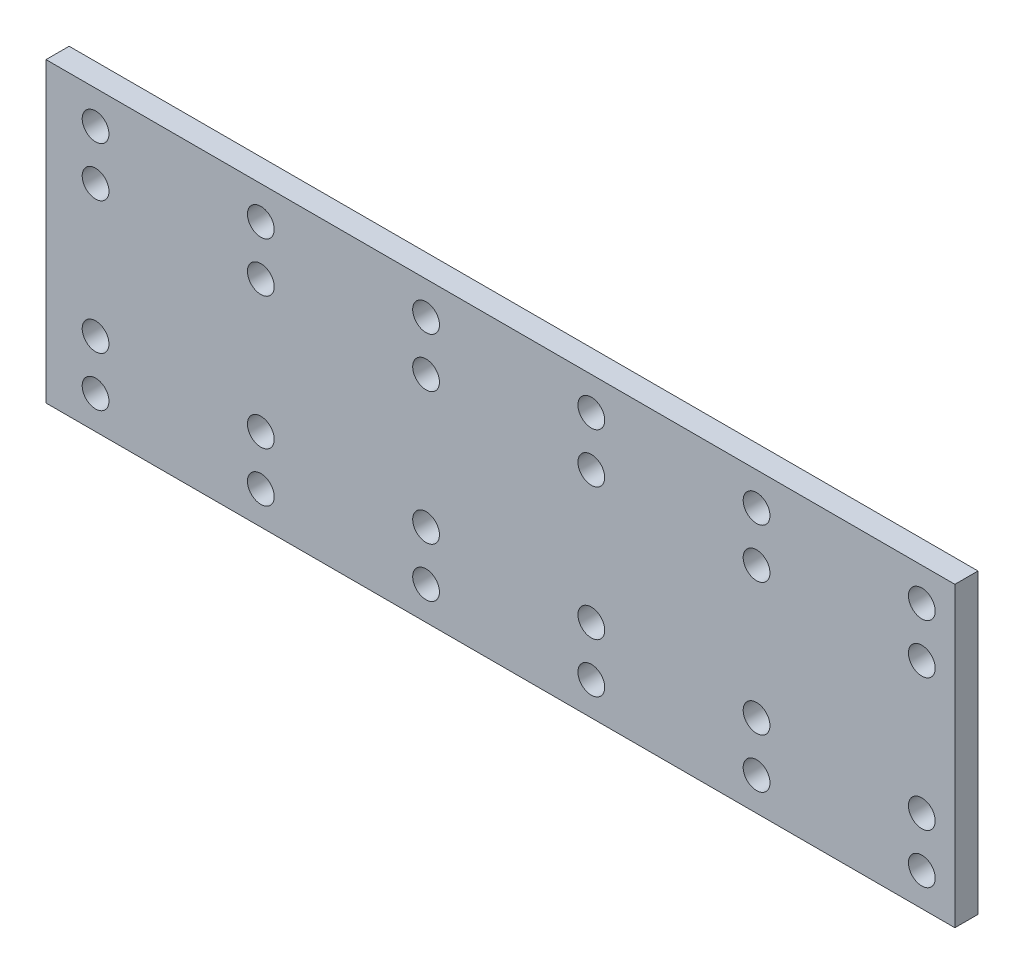
SolidWorks part; units mm, degrees
ref_plane "Front Plane" through (0, 0, 0) normal (0, 0, 1) x (1, 0, 0)
ref_plane "Top Plane" through (0, 0, 0) normal (0, 1, 0) x (1, 0, 0)
ref_plane "Right Plane" through (0, 0, 0) normal (1, 0, 0) x (0, 0, -1)
sketch "Sketch1" plane through (0, 0, 0) normal (0, 0, 1) x (1, 0, 0)
  line L1 (0, 0) -> (275, 0)
  line L2 (0, 0) -> (0, 90)
  line L3 (0, 90) -> (275, 90)
  line L4 (275, 0) -> (275, 90)
  dimension "D1" = 275
  dimension "D2" = 90
extrude "Boss-Extrude1" add sketch "Sketch1" along normal blind 7
sketch "Sketch2" plane through (0, 0, 7) normal (0, 0, 1) x (1, 0, 0)
  line L0 (275, 90) -> (275, 0)
  line L1 (275, 70) -> (0, 70)
  line L2 (0, 90) -> (0, 0) construction
  line L3 (275, 20) -> (0, 20)
  line L4 (275, 65) -> (0, 65)
  line L5 (275, 25) -> (0, 25)
  line L6 (275, 65) -> (265, 65)
  line L7 (265, 65) -> (265, 25)
  line L8 (265, 65) -> (265, 80)
  line L9 (265, 25) -> (265, 10)
  circle A0 centre (265, 65) radius 4.05
  circle A1 centre (265, 25) radius 4.05
  circle A2 centre (215, 65) radius 4.05
  circle A3 centre (215, 25) radius 4.05
  circle A4 centre (165, 65) radius 4.05
  circle A5 centre (165, 25) radius 4.05
  circle A6 centre (115, 65) radius 4.05
  circle A7 centre (115, 25) radius 4.05
  circle A8 centre (65, 65) radius 4.05
  circle A9 centre (65, 25) radius 4.05
  circle A10 centre (265, 80) radius 4.05
  circle A11 centre (265, 10) radius 4.05
  circle A12 centre (215, 80) radius 4.05
  circle A13 centre (215, 10) radius 4.05
  circle A14 centre (165, 80) radius 4.05
  circle A15 centre (165, 10) radius 4.05
  circle A16 centre (115, 80) radius 4.05
  circle A17 centre (115, 10) radius 4.05
  circle A18 centre (65, 80) radius 4.05
  circle A19 centre (65, 10) radius 4.05
  circle A20 centre (15, 80) radius 4.05
  circle A21 centre (15, 25) radius 4.05
  circle A22 centre (15, 10) radius 4.05
  circle A23 centre (15, 65) radius 4.05
  dimension "D6" = 8.1
  dimension "D7" = 8.1
  dimension "D12" = 8.1
  dimension "D13" = 8.1
  dimension "D1" = 50
  dimension "D2" = 20
  dimension "D3" = 5
  dimension "D4" = 5
  dimension "D5" = 10
  dimension "D9" = 70
  dimension "D10" = 15
  dimension "D11" = 15
  dimension "D8" = 5
  dimension "D14" = 5
  dimension "D15" = 2
extrude "Cut-Extrude1" cut sketch "Sketch2" against normal blind 10 contours A11 | A1 | A13 | A3 | A5 | A15 | A4 | A14 | A12 | A2 | A0 | A10 | A6 | A16 | A7 | A17 | A8 | A18 | A19 | A9 | A20 | A23 | A21 | A22
